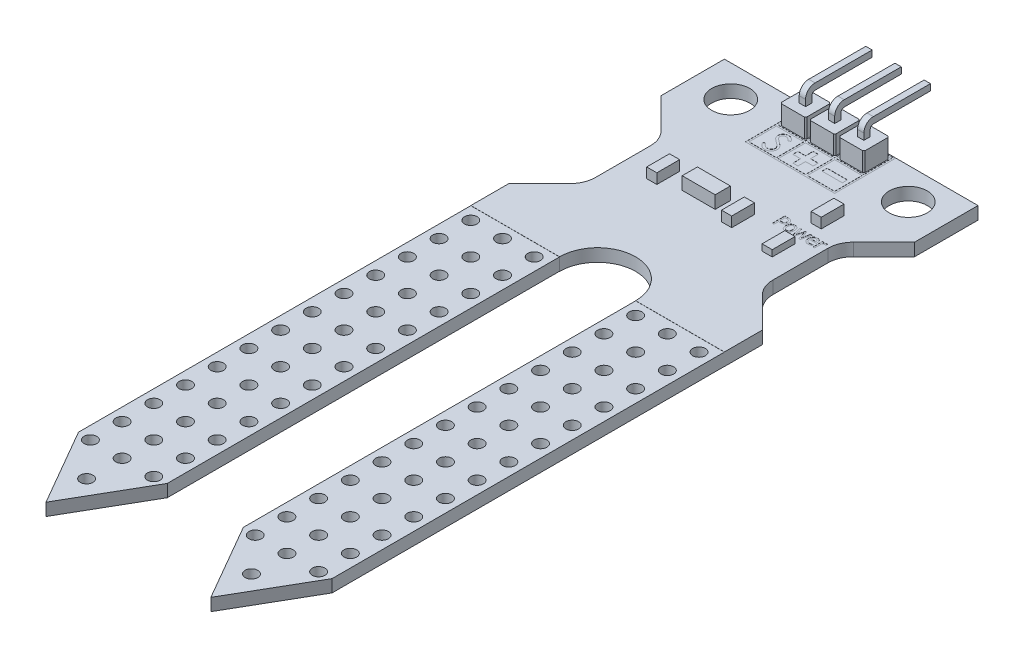
SolidWorks part; units mm, degrees
other "Camera2"
other "Camera4"
ref_plane "Front Plane" through (0, 0, 0) normal (0, 0, 1) x (1, 0, 0)
ref_plane "Top Plane" through (0, 0, 0) normal (0, 1, 0) x (1, 0, 0)
ref_plane "Right Plane" through (0, 0, 0) normal (1, 0, 0) x (0, 0, -1)
sketch "Sketch1" plane through (0, 0, 0) normal (0, 1, 0) x (1, 0, 0)
  line L0 (-10, 0) -> (10, 0)
  line L1 (-10, 0) -> (-10, -57) construction
  line L2 (-10, -57) -> (10, -57) construction
  line L3 (10, -57) -> (10, 0) construction
  line L4 (-10, 0) -> (-10, -5)
  line L5 (-10, -5) -> (-7.5858, -7.4142)
  line L6 (-7, -8.8284) -> (-7, -13.1716)
  line L7 (-7, -11) -> (-10, -11) construction
  line L8 (-10, -17) -> (-7.5858, -14.5858)
  line L9 (-7, -2.5) -> (7, -2.5) construction
  line L10 (0, 0) -> (0, -2.5) construction
  line L11 (-10, -17) -> (-10, -20)
  line L12 (-10, -20) -> (-3, -20)
  line L13 (10, 0) -> (10, -5)
  line L14 (7, -11) -> (10, -11) construction
  line L15 (10, -20) -> (3, -20)
  line L16 (10, -17) -> (10, -20)
  line L17 (10, -17) -> (7.5858, -14.5858)
  line L18 (7, -8.8284) -> (7, -13.1716)
  line L19 (10, -5) -> (7.5858, -7.4142)
  arc A0 (-7.5858, -7.4142) -> (-7, -8.8284) centre (-9, -8.8284) cw
  arc A1 (-7.5858, -14.5858) -> (-7, -13.1716) centre (-9, -13.1716) ccw
  arc A2 (7.5858, -14.5858) -> (7, -13.1716) centre (9, -13.1716) cw
  arc A3 (7.5858, -7.4142) -> (7, -8.8284) centre (9, -8.8284) ccw
  arc A4 (-3, -20) -> (3, -20) centre (0, -20) cw
  point P4 (0, 0)
  point P19 (0, -2.5)
  point P21 (-10, -2.5)
  dimension "D4" = 14
  dimension "D7" = 2
  dimension "D1" = 20
  dimension "D2" = 57
  dimension "D3" = 5
  dimension "D5" = 12
  dimension "D6" = 45
  dimension "D8" = 3
  dimension "D9" = 7
extrude "Base" add sketch "Sketch1" along normal mid plane 1
sketch "Sketch2" plane through (0, 0.5, 0) normal (0, 1, 0) x (1, 0, 0)
  line L0 (0, 0) -> (0, -17) construction
  line L1 (10, 0) -> (-10, 0) construction
  line L2 (7, -2.5) -> (-7, -2.5) construction
  circle A0 centre (-7, -2.5) radius 1.5
  arc A1 (3, -20) -> (-3, -20) centre (0, -20) ccw construction
  circle A2 centre (7, -2.5) radius 1.5
  point P12 (0, -2.5)
  dimension "D1" = 3
  dimension "D3" = 2.5
  dimension "D2" = 14
extrude "Holes" cut sketch "Sketch2" against normal up to next
sketch "Sketch3" plane through (0, 0, 0) normal (0, 1, 0) x (1, 0, 0)
  line L0 (0, 0) -> (0, -57) construction
  line L1 (-10, -20) -> (-3, -20)
  line L2 (-10, -20) -> (-10, -50.9378)
  line L3 (-10, -50.9378) -> (-6.5, -57)
  line L4 (-6.5, -57) -> (-3, -50.9378)
  line L5 (-3, -50.9378) -> (-3, -20)
  line L6 (-6.5, -20) -> (-6.5, -57) construction
  line L7 (-10, -50.9378) -> (-3, -50.9378) construction
  line L8 (10, -50.9378) -> (3, -50.9378) construction
  line L9 (6.5, -20) -> (6.5, -57) construction
  line L10 (3, -50.9378) -> (3, -20)
  line L11 (6.5, -57) -> (3, -50.9378)
  line L12 (10, -50.9378) -> (6.5, -57)
  line L13 (10, -20) -> (10, -50.9378)
  line L14 (10, -20) -> (3, -20)
  point P11 (0, 0)
  dimension "D1" = 57
  dimension "D2" = 30
extrude "Plate" add sketch "Sketch3" along normal mid plane 0.98
sketch "Sketch4" plane through (0, 0.49, 0) normal (0, 1, 0) x (1, 0, 0)
  line L0 (-9, -21) -> (-4, -21) construction
  line L1 (-9, -21) -> (-9, -23.5) construction
  line L2 (-9, -23.5) -> (-6.5, -23.5) construction
  line L3 (-6.5, -51) -> (-6.5, -53.8) construction
  line L4 (-6.5, -20) -> (-6.5, -21) construction
  line L5 (-3, -20) -> (-10, -20) construction
  line L6 (0, 72.5532) -> (0, -72.5532) construction
  line L7 (6.5, -20) -> (6.5, -21) construction
  line L8 (6.5, -51) -> (6.5, -53.8) construction
  line L9 (9, -23.5) -> (6.5, -23.5) construction
  line L10 (9, -21) -> (9, -23.5) construction
  line L11 (9, -21) -> (4, -21) construction
  circle A0 centre (-9, -21) radius 0.5
  circle A1 centre (-6.5, -21) radius 0.5
  circle A2 centre (-4, -21) radius 0.5
  circle A3 centre (-6.5, -23.5) radius 0.5
  circle A4 centre (-4, -23.5) radius 0.5
  circle A5 centre (-6.5, -26) radius 0.5
  circle A6 centre (-4, -26) radius 0.5
  circle A7 centre (-6.5, -28.5) radius 0.5
  circle A8 centre (-4, -28.5) radius 0.5
  circle A9 centre (-6.5, -31) radius 0.5
  circle A10 centre (-4, -31) radius 0.5
  circle A11 centre (-6.5, -33.5) radius 0.5
  circle A12 centre (-4, -33.5) radius 0.5
  circle A13 centre (-6.5, -36) radius 0.5
  circle A14 centre (-4, -36) radius 0.5
  circle A15 centre (-6.5, -38.5) radius 0.5
  circle A16 centre (-4, -38.5) radius 0.5
  circle A17 centre (-6.5, -41) radius 0.5
  circle A18 centre (-4, -41) radius 0.5
  circle A19 centre (-6.5, -43.5) radius 0.5
  circle A20 centre (-4, -43.5) radius 0.5
  circle A21 centre (-6.5, -46) radius 0.5
  circle A22 centre (-4, -46) radius 0.5
  circle A23 centre (-6.5, -48.5) radius 0.5
  circle A24 centre (-4, -48.5) radius 0.5
  circle A25 centre (-6.5, -51) radius 0.5
  circle A26 centre (-4, -51) radius 0.5
  circle A27 centre (-9, -23.5) radius 0.5
  circle A28 centre (-9, -26) radius 0.5
  circle A29 centre (-9, -28.5) radius 0.5
  circle A30 centre (-9, -31) radius 0.5
  circle A31 centre (-9, -33.5) radius 0.5
  circle A32 centre (-9, -36) radius 0.5
  circle A33 centre (-9, -38.5) radius 0.5
  circle A34 centre (-9, -41) radius 0.5
  circle A35 centre (-9, -43.5) radius 0.5
  circle A36 centre (-9, -46) radius 0.5
  circle A37 centre (-9, -48.5) radius 0.5
  circle A38 centre (-9, -51) radius 0.5
  circle A39 centre (-6.5, -53.8) radius 0.5
  circle A40 centre (6.5, -53.8) radius 0.5
  circle A41 centre (9, -51) radius 0.5
  circle A42 centre (9, -48.5) radius 0.5
  circle A43 centre (9, -46) radius 0.5
  circle A44 centre (9, -43.5) radius 0.5
  circle A45 centre (9, -41) radius 0.5
  circle A46 centre (9, -38.5) radius 0.5
  circle A47 centre (9, -36) radius 0.5
  circle A48 centre (9, -33.5) radius 0.5
  circle A49 centre (9, -31) radius 0.5
  circle A50 centre (9, -28.5) radius 0.5
  circle A51 centre (9, -26) radius 0.5
  circle A52 centre (9, -23.5) radius 0.5
  circle A53 centre (4, -51) radius 0.5
  circle A54 centre (6.5, -51) radius 0.5
  circle A55 centre (4, -48.5) radius 0.5
  circle A56 centre (6.5, -48.5) radius 0.5
  circle A57 centre (4, -46) radius 0.5
  circle A58 centre (6.5, -46) radius 0.5
  circle A59 centre (4, -43.5) radius 0.5
  circle A60 centre (6.5, -43.5) radius 0.5
  circle A61 centre (4, -41) radius 0.5
  circle A62 centre (6.5, -41) radius 0.5
  circle A63 centre (4, -38.5) radius 0.5
  circle A64 centre (6.5, -38.5) radius 0.5
  circle A65 centre (4, -36) radius 0.5
  circle A66 centre (6.5, -36) radius 0.5
  circle A67 centre (4, -33.5) radius 0.5
  circle A68 centre (6.5, -33.5) radius 0.5
  circle A69 centre (4, -31) radius 0.5
  circle A70 centre (6.5, -31) radius 0.5
  circle A71 centre (4, -28.5) radius 0.5
  circle A72 centre (6.5, -28.5) radius 0.5
  circle A73 centre (4, -26) radius 0.5
  circle A74 centre (6.5, -26) radius 0.5
  circle A75 centre (4, -23.5) radius 0.5
  circle A76 centre (6.5, -23.5) radius 0.5
  circle A77 centre (4, -21) radius 0.5
  circle A78 centre (6.5, -21) radius 0.5
  circle A79 centre (9, -21) radius 0.5
  point P89 (0, 0)
  point P170 (-6.5, -23.5)
  dimension "D1" = 1
  dimension "D8" = 2.8
  dimension "D2" = 5
  dimension "D3" = 1
  dimension "D6" = 2.5
  dimension "D4" = 3
  dimension "D5" = 13
extrude "Plate holes" cut sketch "Sketch4" against normal through all
sketch "Sketch5" plane through (0, 0.5, 0) normal (0, 1, 0) x (1, 0, 0)
  line L0 (-7, -2.5) -> (7, -2.5) construction
  line L1 (-3.2, -0.3) -> (-3.3, -0.4)
  line L2 (-3.2, -0.3) -> (-1.4, -0.3)
  line L3 (-3.3, -0.4) -> (-3.3, -2.2)
  line L4 (-3.2, -2.3) -> (-1.4, -2.3)
  line L5 (-1.3, -0.4) -> (-1.3, -2.2)
  line L6 (-3.3, -0.3) -> (-1.3, -2.3) construction
  line L7 (-3.3, -2.3) -> (-1.3, -0.3) construction
  line L8 (-1.4, -0.3) -> (-1.3, -0.4)
  line L9 (-3.3, -2.2) -> (-3.2, -2.3)
  line L10 (-1.3, -2.2) -> (-1.4, -2.3)
  line L11 (-0.9, -0.3) -> (-1, -0.4)
  line L12 (-0.9, -0.3) -> (0.9, -0.3)
  line L13 (-1, -0.4) -> (-1, -2.2)
  line L14 (-0.9, -2.3) -> (0.9, -2.3)
  line L15 (1, -0.4) -> (1, -2.2)
  line L16 (0.9, -0.3) -> (1, -0.4)
  line L17 (-1, -2.2) -> (-0.9, -2.3)
  line L18 (1, -2.2) -> (0.9, -2.3)
  line L19 (-1, -0.3) -> (1, -2.3) construction
  line L20 (-1, -2.3) -> (1, -0.3) construction
  line L21 (1.4, -0.3) -> (1.3, -0.4)
  line L22 (1.4, -0.3) -> (3.2, -0.3)
  line L23 (1.3, -0.4) -> (1.3, -2.2)
  line L24 (1.4, -2.3) -> (3.2, -2.3)
  line L25 (3.3, -0.4) -> (3.3, -2.2)
  line L26 (3.2, -0.3) -> (3.3, -0.4)
  line L27 (1.3, -2.2) -> (1.4, -2.3)
  line L28 (3.3, -2.2) -> (3.2, -2.3)
  line L29 (1.3, -0.3) -> (3.3, -2.3) construction
  line L30 (1.3, -2.3) -> (3.3, -0.3) construction
  line L31 (0, -2.3) -> (0, -2.5) construction
  point P4 (-2.3, -1.3)
  point P19 (0, -1.3)
  point P32 (2.3, -1.3)
  point P45 (0, 0)
  point P46 (0, 0)
  dimension "D1" = 2
  dimension "D2" = 3
  dimension "D3" = 0.2
  dimension "D8" = 0.3
extrude "Socket" add sketch "Sketch5" along normal blind 1.5
sketch "Sketch6" plane through (0, 2, 0) normal (0, 1, 0) x (1, 0, 0)
  line L0 (-2.3, -1.3) -> (-2.3, -0.3) construction
  line L1 (-2.6, -1.6) -> (-2, -1.6)
  line L2 (-2.6, -1.6) -> (-2.6, -1)
  line L3 (-2.6, -1) -> (-2, -1)
  line L4 (-2, -1.6) -> (-2, -1)
  line L5 (-2.6, -1.6) -> (-2, -1) construction
  line L6 (-2.6, -1) -> (-2, -1.6) construction
  line L8 (-1.4, -0.3) -> (-3.2, -0.3) construction
  line L9 (-2.3, -1.3) -> (-3.3, -1.3) construction
  line L10 (-3.3, -0.4) -> (-3.3, -2.2) construction
  point P0 (-2.3, -1.3)
  dimension "D1" = 0.6
sketch "Sketch7" plane through (0, 0, 0) normal (1, 0, 0) x (0, 0, -1)
  line L0 (-1.3, 2) -> (-1.3, 2.5) construction
  line L1 (-0.4, 2) -> (-2.2, 2) construction
  line L2 (-0.8, 3) -> (3.7, 3) construction
  line L3 (-1.05, 2) -> (-1.05, 2.5)
  line L4 (-0.8, 2.75) -> (3.7, 2.75)
  line L5 (-1.55, 2) -> (-1.55, 2.5)
  line L6 (-0.8, 3.25) -> (3.7, 3.25)
  line L7 (3.7, 3.25) -> (3.7, 2.75)
  line L8 (-1.05, 2) -> (-1.55, 2)
  arc A0 (-0.8, 3) -> (-1.3, 2.5) centre (-0.8, 2.5) ccw construction
  arc A1 (-0.8, 2.75) -> (-1.05, 2.5) centre (-0.8, 2.5) ccw
  arc A2 (-0.8, 3.25) -> (-1.55, 2.5) centre (-0.8, 2.5) ccw
  dimension "D2" = 0.5
  dimension "D1" = 0.5
  dimension "D3" = 5
  dimension "D4" = 0.25
  dimension "D5" = 0.25
extrude "Power pin" add sketch "Sketch7" along normal mid plane 0.5
pattern_linear "LPattern2" count 2 spacing 2.3 along (1, 0, 0) count 2 spacing 2.3 along (-1, 0, 0) of "Power pin"
sketch "Sketch9" plane through (0, 0.5, 0) normal (0, 1, 0) x (1, 0, 0)
  line L0 (-0.2, -3.8) -> (-0.2, -4.4)
  line L1 (-3.38, -2.38) -> (-1.22, -2.38)
  line L2 (-3.38, -2.38) -> (-3.38, -0.22)
  line L3 (-3.38, -0.22) -> (-1.22, -0.22)
  line L4 (-1.22, -2.38) -> (-1.22, -0.22)
  line L5 (-3.2, -2.3) -> (-1.4, -2.3) construction
  line L6 (-1.4, -0.3) -> (-3.2, -0.3) construction
  line L7 (-3.3, -0.4) -> (-3.3, -2.2) construction
  line L8 (-1.08, -2.38) -> (1.08, -2.38)
  line L9 (-1.08, -2.38) -> (-1.08, -0.22)
  line L10 (-1.08, -0.22) -> (1.08, -0.22)
  line L11 (1.08, -2.38) -> (1.08, -0.22)
  line L12 (1.22, -2.38) -> (3.38, -2.38)
  line L13 (1.22, -2.38) -> (1.22, -0.22)
  line L14 (1.22, -0.22) -> (3.38, -0.22)
  line L15 (3.38, -2.38) -> (3.38, -0.22)
  line L16 (-1.08, -4.68) -> (1.08, -4.68)
  line L17 (-1.08, -4.68) -> (-1.08, -2.52)
  line L18 (-1.08, -2.52) -> (1.08, -2.52)
  line L19 (1.08, -4.68) -> (1.08, -2.52)
  line L20 (1.22, -4.68) -> (3.38, -4.68)
  line L21 (1.22, -4.68) -> (1.22, -2.52)
  line L22 (1.22, -2.52) -> (3.38, -2.52)
  line L23 (3.38, -4.68) -> (3.38, -2.52)
  line L24 (-3.38, -4.68) -> (-1.22, -4.68)
  line L25 (-3.38, -4.68) -> (-3.38, -2.52)
  line L26 (-3.38, -2.52) -> (-1.22, -2.52)
  line L27 (-1.22, -4.68) -> (-1.22, -2.52)
  line L28 (-3.38, -0.22) -> (-3.38, -0.08) construction
  line L29 (-3.52, -0.08) -> (3.52, -0.08)
  line L30 (-3.52, -0.08) -> (-3.52, -4.82)
  line L31 (-3.52, -4.82) -> (3.52, -4.82)
  line L32 (3.52, -0.08) -> (3.52, -4.82)
  line L33 (-3.38, -0.22) -> (-3.52, -0.22) construction
  line L34 (-3.38, -4.68) -> (-3.38, -4.82) construction
  line L35 (3.38, -0.22) -> (3.52, -0.22) construction
  line L37 (1.5, -3.4) -> (1.5, -3.8)
  line L38 (1.5, -3.8) -> (3.1, -3.8)
  line L39 (3.1, -3.8) -> (3.1, -3.4)
  line L40 (3.1, -3.4) -> (1.5, -3.4)
  line L41 (-0.8, -3.4) -> (-0.8, -3.8)
  line L42 (-0.8, -3.8) -> (-0.2, -3.8)
  line L43 (0.8, -3.8) -> (0.8, -3.4)
  line L44 (0.8, -3.4) -> (0.2, -3.4)
  line L45 (-0.2, -2.8) -> (0.2, -2.8)
  line L46 (-0.2, -2.8) -> (-0.2, -3.4)
  line L47 (-0.2, -4.4) -> (0.2, -4.4)
  line L48 (0.2, -2.8) -> (0.2, -3.4)
  line L49 (-0.2, -3.4) -> (-0.8, -3.4)
  line L50 (0.2, -3.8) -> (0.2, -4.4)
  line L51 (0.2, -3.8) -> (0.8, -3.8)
  line L52 (3.3426, -8.9613) -> (3.2278, -8.9613)
  line L53 (3.2278, -8.9613) -> (3.2278, -9.3284)
  line L54 (3.2278, -9.3284) -> (3.1013, -9.3284)
  line L55 (3.1013, -9.3284) -> (3.1013, -8.3284)
  line L56 (3.1013, -8.3284) -> (3.353, -8.3284)
  line L57 (3.3402, -8.4424) -> (3.2278, -8.4424)
  line L58 (3.2278, -8.4424) -> (3.2278, -8.8474)
  line L59 (3.2278, -8.8474) -> (3.3202, -8.8474)
  line L60 (5.4937, -8.5816) -> (5.3072, -9.3284)
  line L61 (5.3072, -9.3284) -> (5.1926, -9.3284)
  line L62 (5.1926, -9.3284) -> (5.0127, -8.7527)
  line L63 (5.0127, -8.7527) -> (4.8341, -9.3284)
  line L64 (4.8341, -9.3284) -> (4.7201, -9.3284)
  line L65 (4.7201, -9.3284) -> (4.5316, -8.5816)
  line L66 (4.5316, -8.5816) -> (4.6622, -8.5816)
  line L67 (4.6622, -8.5816) -> (4.7905, -9.1599)
  line L68 (4.7905, -9.1599) -> (4.9652, -8.5816)
  line L69 (4.9652, -8.5816) -> (5.0674, -8.5816)
  line L70 (5.0674, -8.5816) -> (5.2466, -9.1599)
  line L71 (5.2466, -9.1599) -> (5.3631, -8.5816)
  line L72 (5.3631, -8.5816) -> (5.4937, -8.5816)
  line L73 (6.2025, -8.8935) -> (6.2025, -8.9613)
  line L74 (6.2025, -8.9613) -> (5.6835, -8.9613)
  line L75 (6.1826, -9.1386) -> (6.1899, -9.1386)
  line L76 (6.1899, -9.1386) -> (6.1899, -9.2782)
  line L77 (5.6835, -8.8601) -> (6.0759, -8.8601)
  line L78 (6.7215, -8.7082) -> (6.715, -8.7082)
  line L79 (6.4557, -8.7962) -> (6.4557, -9.3284)
  line L80 (6.4557, -9.3284) -> (6.3291, -9.3284)
  line L81 (6.3291, -9.3284) -> (6.3291, -8.5816)
  line L82 (6.3291, -8.5816) -> (6.4557, -8.5816)
  line L83 (6.4557, -8.5816) -> (6.4557, -8.6925)
  line L84 (6.7215, -8.5853) -> (6.7215, -8.7082)
  line L85 (-2.7938, -4.1828) -> (-2.6417, -4.0915)
  line L86 (-1.7554, -2.9885) -> (-1.9014, -3.0992)
  spline S0 degree 3 poles (3.7342, -8.6326) (3.7344, -8.6541) (3.7312, -8.6861) (3.7215, -8.7275) (3.7111, -8.7571) (3.6985, -8.7853) (3.678, -8.8198) (3.6595, -8.8432) (3.6454, -8.8569) knots 0 0 0 0 0.260382 0.387742 0.514624 0.640166 0.761611 1 1 1 1
  spline S1 degree 3 poles (3.6454, -8.8569) (3.6282, -8.8742) (3.5993, -8.8968) (3.5564, -8.9209) (3.5216, -8.936) (3.4831, -8.9475) (3.4234, -8.9589) (3.3757, -8.9613) (3.3426, -8.9613) knots 0 0 0 0 0.221352 0.332954 0.446759 0.566652 0.698228 1 1 1 1
  spline S2 degree 3 poles (3.353, -8.3284) (3.3806, -8.3286) (3.4203, -8.3298) (3.4708, -8.3364) (3.504, -8.3429) (3.5348, -8.3514) (3.5726, -8.3658) (3.5988, -8.3803) (3.6149, -8.3915) knots 0 0 0 0 0.301816 0.435226 0.557564 0.673138 0.784559 1 1 1 1
  spline S3 degree 3 poles (3.6149, -8.3915) (3.6332, -8.404) (3.6584, -8.4259) (3.6857, -8.4609) (3.7033, -8.4893) (3.7173, -8.5207) (3.7309, -8.5683) (3.7342, -8.6065) (3.7342, -8.6326) knots 0 0 0 0 0.236653 0.354095 0.472429 0.593575 0.720488 1 1 1 1
  spline S4 degree 3 poles (3.5949, -8.6358) (3.5948, -8.6193) (3.5931, -8.5951) (3.5852, -8.5648) (3.5772, -8.5443) (3.567, -8.5256) (3.5496, -8.5031) (3.5337, -8.4887) (3.5216, -8.4811) knots 0 0 0 0 0.276791 0.40364 0.52478 0.643556 0.760318 1 1 1 1
  spline S5 degree 3 poles (3.5216, -8.4811) (3.5108, -8.4736) (3.4927, -8.465) (3.4672, -8.456) (3.4461, -8.4509) (3.4232, -8.4469) (3.3877, -8.4431) (3.3597, -8.4425) (3.3402, -8.4424) knots 0 0 0 0 0.208675 0.317736 0.431465 0.554189 0.688523 1 1 1 1
  spline S6 degree 3 poles (3.3202, -8.8474) (3.345, -8.8475) (3.3804, -8.8462) (3.4247, -8.8404) (3.4525, -8.8348) (3.4773, -8.8269) (3.5069, -8.813) (3.5261, -8.7981) (3.5374, -8.7869) knots 0 0 0 0 0.321499 0.457599 0.578008 0.68845 0.794252 1 1 1 1
  spline S7 degree 3 poles (3.5374, -8.7869) (3.5471, -8.7772) (3.5599, -8.7612) (3.5734, -8.7381) (3.5815, -8.7202) (3.5877, -8.7012) (3.5936, -8.6731) (3.595, -8.6509) (3.5949, -8.6358) knots 0 0 0 0 0.248146 0.366465 0.48252 0.601376 0.726647 1 1 1 1
  spline S8 degree 3 poles (4.4684, -8.9554) (4.4684, -8.9855) (4.4659, -9.0294) (4.4562, -9.0856) (4.4463, -9.124) (4.4336, -9.1597) (4.4176, -9.1926) (4.399, -9.2228) (4.3776, -9.2501) (4.3538, -9.2745) (4.328, -9.2959) (4.3001, -9.3137) (4.2705, -9.3285) (4.2389, -9.3398) (4.1934, -9.3507) (4.1577, -9.3539) (4.1335, -9.3537) knots 0 0 0 0 0.153334 0.223622 0.290634 0.354958 0.416591 0.476661 0.53556 0.593318 0.64991 0.70585 0.761767 0.818223 0.876674 1 1 1 1
  spline S9 degree 3 poles (4.1335, -9.3537) (4.1086, -9.354) (4.0722, -9.3506) (4.0256, -9.3395) (3.9936, -9.3274) (3.9635, -9.3124) (3.9356, -9.2939) (3.91, -9.2719) (3.8864, -9.2468) (3.8656, -9.2187) (3.8472, -9.1882) (3.8318, -9.1552) (3.8191, -9.1199) (3.8096, -9.0821) (3.7997, -9.0273) (3.7976, -8.9845) (3.7975, -8.9554) knots 0 0 0 0 0.126624 0.185762 0.243469 0.300245 0.356694 0.413633 0.472086 0.531601 0.591562 0.653162 0.716692 0.782593 0.851506 1 1 1 1
  spline S10 degree 3 poles (3.7975, -8.9554) (3.7974, -8.9255) (3.7998, -8.8818) (3.8099, -8.8258) (3.8199, -8.7875) (3.8327, -8.7518) (3.8488, -8.7188) (3.8676, -8.6884) (3.8892, -8.6608) (3.9134, -8.6364) (3.9393, -8.6148) (3.9673, -8.5967) (3.9969, -8.5816) (4.0286, -8.5706) (4.0739, -8.5591) (4.1095, -8.5563) (4.1335, -8.5563) knots 0 0 0 0 0.152158 0.222426 0.289447 0.353383 0.415396 0.47586 0.535165 0.593567 0.650568 0.706628 0.762633 0.819341 0.87748 1 1 1 1
  spline S11 degree 3 poles (4.1335, -8.5563) (4.1577, -8.5561) (4.1934, -8.5593) (4.239, -8.5702) (4.2705, -8.5818) (4.3001, -8.5967) (4.328, -8.6148) (4.3539, -8.6361) (4.3776, -8.6607) (4.399, -8.6882) (4.4177, -8.7185) (4.4335, -8.7514) (4.4464, -8.7871) (4.4562, -8.8254) (4.4658, -8.8816) (4.4685, -8.9255) (4.4684, -8.9554) knots 0 0 0 0 0.123252 0.181668 0.238205 0.294238 0.350327 0.406885 0.464849 0.523978 0.584011 0.64591 0.70988 0.776851 0.847428 1 1 1 1
  spline S12 degree 3 poles (4.3418, -8.9554) (4.3418, -8.9328) (4.3406, -8.9) (4.3344, -8.8581) (4.3289, -8.8299) (4.3211, -8.8041) (4.3119, -8.7806) (4.3007, -8.7595) (4.2882, -8.7406) (4.2737, -8.7241) (4.2581, -8.7094) (4.2407, -8.6974) (4.2221, -8.6873) (4.202, -8.6796) (4.1725, -8.672) (4.1492, -8.6704) (4.1335, -8.6702) knots 0 0 0 0 0.168865 0.245064 0.316508 0.383414 0.446027 0.505125 0.561591 0.615756 0.66878 0.721159 0.77321 0.826581 0.882058 1 1 1 1
  spline S13 degree 3 poles (4.1335, -8.6702) (4.1177, -8.6705) (4.0943, -8.672) (4.0648, -8.6796) (4.0445, -8.6873) (4.0257, -8.6973) (4.0083, -8.7095) (3.9925, -8.7241) (3.9779, -8.7405) (3.9653, -8.7595) (3.9541, -8.7806) (3.9446, -8.8041) (3.9372, -8.83) (3.9313, -8.8581) (3.9253, -8.9) (3.924, -8.9328) (3.9241, -8.9554) knots 0 0 0 0 0.118168 0.173523 0.227235 0.279605 0.331868 0.385137 0.439506 0.495848 0.554814 0.617473 0.684091 0.755478 0.831508 1 1 1 1
  spline S14 degree 3 poles (3.9241, -8.9554) (3.924, -8.9773) (3.9254, -9.0093) (3.9314, -9.0502) (3.9372, -9.0779) (3.9446, -9.1037) (3.9542, -9.127) (3.9653, -9.1484) (3.9779, -9.1677) (3.9924, -9.1847) (4.0083, -9.1996) (4.0258, -9.2119) (4.0444, -9.2223) (4.0647, -9.2302) (4.0943, -9.2377) (4.1177, -9.2398) (4.1335, -9.2398) knots 0 0 0 0 0.164255 0.239131 0.309846 0.376265 0.439182 0.498828 0.556224 0.611938 0.665761 0.718524 0.771581 0.825693 0.881275 1 1 1 1
  spline S15 degree 3 poles (4.1335, -9.2398) (4.1492, -9.2396) (4.1723, -9.2379) (4.2017, -9.2305) (4.2216, -9.2224) (4.2403, -9.2126) (4.2575, -9.2003) (4.2734, -9.1858) (4.2877, -9.169) (4.3007, -9.1502) (4.3117, -9.1289) (4.3209, -9.1053) (4.3286, -9.0796) (4.3345, -9.0517) (4.3405, -9.0102) (4.3418, -8.9777) (4.3418, -8.9554) knots 0 0 0 0 0.117813 0.172983 0.22624 0.278888 0.331025 0.384578 0.439285 0.496204 0.555922 0.618729 0.685842 0.756642 0.832586 1 1 1 1
  spline S16 degree 3 poles (5.9337, -9.3411) (5.9055, -9.3412) (5.8641, -9.3381) (5.8111, -9.3279) (5.775, -9.3167) (5.7412, -9.3027) (5.7101, -9.2851) (5.6813, -9.2647) (5.6553, -9.241) (5.6322, -9.2144) (5.6118, -9.1852) (5.5948, -9.1532) (5.581, -9.1185) (5.57, -9.0813) (5.5596, -9.0266) (5.5571, -8.9838) (5.557, -8.9546) knots 0 0 0 0 0.138011 0.202055 0.263381 0.322416 0.38038 0.437398 0.494395 0.551685 0.609308 0.668092 0.728495 0.79127 0.85721 1 1 1 1
  spline S17 degree 3 poles (5.557, -8.9546) (5.5572, -8.9257) (5.5594, -8.8831) (5.5697, -8.8286) (5.5802, -8.791) (5.5936, -8.7557) (5.6101, -8.7227) (5.6296, -8.692) (5.6519, -8.6639) (5.6768, -8.6387) (5.7036, -8.6166) (5.7323, -8.5978) (5.7628, -8.5826) (5.7953, -8.5708) (5.8417, -8.5592) (5.8783, -8.5565) (5.9029, -8.5563) knots 0 0 0 0 0.146259 0.214368 0.279724 0.343168 0.404962 0.465739 0.526162 0.585964 0.644156 0.701412 0.75874 0.816144 0.875498 1 1 1 1
  spline S18 degree 3 poles (5.9029, -8.5563) (5.9248, -8.5562) (5.9569, -8.5583) (5.9978, -8.567) (6.0259, -8.5756) (6.0519, -8.5873) (6.085, -8.606) (6.1064, -8.6252) (6.1197, -8.6388) knots 0 0 0 0 0.275081 0.402883 0.524391 0.643013 0.760604 1 1 1 1
  spline S19 degree 3 poles (6.1197, -8.6388) (6.1335, -8.6529) (6.151, -8.6774) (6.17, -8.7133) (6.1819, -8.7432) (6.1912, -8.776) (6.2005, -8.8262) (6.2024, -8.866) (6.2025, -8.8935) knots 0 0 0 0 0.215476 0.326952 0.443318 0.566199 0.699559 1 1 1 1
  spline S20 degree 3 poles (5.6835, -8.9613) (5.6834, -8.9817) (5.6853, -9.0114) (5.6924, -9.0494) (5.6994, -9.0752) (5.7087, -9.0991) (5.72, -9.1211) (5.7335, -9.1411) (5.7491, -9.1592) (5.7663, -9.1753) (5.7854, -9.1891) (5.8059, -9.2009) (5.828, -9.2107) (5.8518, -9.2179) (5.8863, -9.2251) (5.9133, -9.2274) (5.9318, -9.2272) knots 0 0 0 0 0.14768 0.215278 0.279761 0.341367 0.400591 0.458795 0.516089 0.572912 0.629707 0.686449 0.744451 0.804022 0.866557 1 1 1 1
  spline S21 degree 3 poles (5.9318, -9.2272) (5.9591, -9.227) (6.012, -9.2213) (6.0623, -9.2043) (6.0856, -9.1943) knots 0 0 0 0 0.518474 1 1 1 1
  spline S22 degree 3 poles (6.0856, -9.1943) (6.1053, -9.1856) (6.1392, -9.1694) (6.17, -9.1482) (6.1826, -9.1386) knots 0 0 0 0 0.577022 1 1 1 1
  spline S23 degree 3 poles (6.1899, -9.2782) (6.1816, -9.2814) (6.1686, -9.2865) (6.1502, -9.2938) (6.1209, -9.3056) (6.096, -9.3149) (6.0759, -9.3203) knots 0 0 0 0 0.218524 0.346372 0.486611 1 1 1 1
  spline S24 degree 3 poles (6.0759, -9.3203) (6.0539, -9.3262) (6.0265, -9.3331) (5.9927, -9.3384) (5.9675, -9.3404) (5.9477, -9.341) (5.9337, -9.3411) knots 0 0 0 0 0.475716 0.586628 0.710511 1 1 1 1
  spline S25 degree 3 poles (6.0759, -8.8601) (6.0758, -8.8446) (6.0738, -8.8223) (6.069, -8.7938) (6.0641, -8.7749) (6.0586, -8.7574) (6.049, -8.7366) (6.0406, -8.7221) (6.0334, -8.7137) knots 0 0 0 0 0.299598 0.432962 0.557938 0.676116 0.788008 1 1 1 1
  spline S26 degree 3 poles (6.0334, -8.7137) (6.0262, -8.7046) (6.0135, -8.6924) (5.9937, -8.6794) (5.9771, -8.6716) (5.9589, -8.6651) (5.9307, -8.6589) (5.9081, -8.6578) (5.8926, -8.6575) knots 0 0 0 0 0.22125 0.334031 0.45002 0.571455 0.703086 1 1 1 1
  spline S27 degree 3 poles (5.8926, -8.6575) (5.8772, -8.6575) (5.8549, -8.6593) (5.8267, -8.6653) (5.808, -8.672) (5.7907, -8.6802) (5.7689, -8.6936) (5.7538, -8.7059) (5.7447, -8.7151) knots 0 0 0 0 0.282218 0.410057 0.529593 0.645 0.761338 1 1 1 1
  spline S28 degree 3 poles (5.7447, -8.7151) (5.7355, -8.7243) (5.7235, -8.7396) (5.7099, -8.7614) (5.7019, -8.7788) (5.695, -8.7971) (5.6882, -8.8242) (5.6844, -8.8454) (5.6835, -8.8601) knots 0 0 0 0 0.242625 0.360813 0.479168 0.599866 0.725826 1 1 1 1
  spline S29 degree 3 poles (6.715, -8.7082) (6.7052, -8.7082) (6.6831, -8.7082) (6.6609, -8.7082) (6.6485, -8.7082) knots 0 0 0 0 0.440476 1 1 1 1
  spline S30 degree 3 poles (6.6485, -8.7082) (6.6318, -8.7082) (6.6064, -8.7111) (6.5734, -8.7203) (6.5486, -8.73) (6.5243, -8.7425) (6.4921, -8.7632) (6.4697, -8.7821) (6.4557, -8.7962) knots 0 0 0 0 0.230943 0.349875 0.471982 0.597666 0.726082 1 1 1 1
  spline S31 degree 3 poles (6.4557, -8.6925) (6.476, -8.6742) (6.5058, -8.6494) (6.546, -8.6216) (6.5728, -8.6067) (6.5982, -8.5954) (6.6306, -8.5852) (6.6552, -8.5815) (6.6715, -8.5816) knots 0 0 0 0 0.33091 0.468651 0.589975 0.700616 0.804235 1 1 1 1
  spline S32 degree 3 poles (6.6715, -8.5816) (6.681, -8.5815) (6.6978, -8.5818) (6.7144, -8.5844) (6.7215, -8.5853) knots 0 0 0 0 0.571302 1 1 1 1
  spline S33 degree 3 poles (-2.6417, -4.0915) (-2.6153, -4.1373) (-2.5737, -4.2014) (-2.5083, -4.2741) (-2.4595, -4.3167) (-2.4089, -4.3502) (-2.3395, -4.3818) (-2.2835, -4.3916) (-2.2465, -4.3915) knots 0 0 0 0 0.304646 0.438547 0.562322 0.677433 0.786897 1 1 1 1
  spline S34 degree 3 poles (-2.2465, -4.3915) (-2.2152, -4.3918) (-2.1685, -4.3863) (-2.1086, -4.369) (-2.0661, -4.3506) (-2.0265, -4.3283) (-1.9917, -4.3014) (-1.9617, -4.2712) (-1.9371, -4.2376) (-1.9182, -4.2014) (-1.8989, -4.152) (-1.8943, -4.1124) (-1.8938, -4.0865) knots 0 0 0 0 0.18093 0.270088 0.360156 0.448343 0.532666 0.613834 0.693982 0.772716 0.849335 1 1 1 1
  spline S35 degree 3 poles (-1.8938, -4.0865) (-1.8937, -4.056) (-1.906, -3.9924) (-1.9388, -3.9366) (-1.9584, -3.9098) knots 0 0 0 0 0.477158 1 1 1 1
  spline S36 degree 3 poles (-1.9584, -3.9098) (-1.975, -3.8879) (-2.003, -3.8547) (-2.0466, -3.8124) (-2.0846, -3.7769) (-2.1279, -3.7407) (-2.1931, -3.6875) (-2.2463, -3.6492) (-2.2829, -3.6228) knots 0 0 0 0 0.18953 0.299198 0.418926 0.548376 0.688136 1 1 1 1
  spline S37 degree 3 poles (-2.2829, -3.6228) (-2.3193, -3.5973) (-2.3703, -3.5595) (-2.434, -3.5102) (-2.4737, -3.4782) (-2.5078, -3.4491) (-2.5433, -3.4173) (-2.5654, -3.3933) (-2.5779, -3.378) knots 0 0 0 0 0.347082 0.495568 0.628357 0.74552 0.845831 1 1 1 1
  spline S38 degree 3 poles (-2.5779, -3.378) (-2.5938, -3.3574) (-2.616, -3.3257) (-2.6397, -3.2806) (-2.6534, -3.2464) (-2.665, -3.2118) (-2.6755, -3.1646) (-2.6786, -3.1282) (-2.6785, -3.1039) knots 0 0 0 0 0.262559 0.388264 0.512667 0.633722 0.755394 1 1 1 1
  spline S39 degree 3 poles (-2.6785, -3.1039) (-2.6786, -3.0663) (-2.6714, -3.0102) (-2.6475, -2.9396) (-2.6227, -2.8901) (-2.5906, -2.8448) (-2.5536, -2.8034) (-2.5095, -2.7685) (-2.461, -2.738) (-2.408, -2.7142) (-2.3334, -2.69) (-2.2742, -2.6844) (-2.235, -2.6838) knots 0 0 0 0 0.16578 0.24628 0.327461 0.408797 0.489715 0.571376 0.655523 0.741019 0.826547 1 1 1 1
  spline S40 degree 3 poles (-2.235, -2.6838) (-2.1928, -2.6838) (-2.1296, -2.6915) (-2.0498, -2.7196) (-2.0017, -2.7434) (-1.9641, -2.7671) (-1.9354, -2.7887) (-1.9064, -2.8136) (-1.8767, -2.8418) (-1.8469, -2.8736) (-1.8052, -2.9219) (-1.775, -2.9609) (-1.7554, -2.9885) knots 0 0 0 0 0.213252 0.31883 0.426794 0.483646 0.543604 0.608308 0.677127 0.750686 0.828713 1 1 1 1
  spline S41 degree 3 poles (-1.9014, -3.0992) (-1.9182, -3.0772) (-1.9435, -3.0462) (-1.9773, -3.0074) (-2.0012, -2.9831) (-2.0236, -2.9611) (-2.0452, -2.9423) (-2.0659, -2.9265) (-2.092, -2.9096) (-2.1248, -2.8929) (-2.1799, -2.8738) (-2.2237, -2.8686) (-2.253, -2.8685) knots 0 0 0 0 0.189629 0.274184 0.352183 0.423199 0.488551 0.548473 0.60144 0.701198 0.799592 1 1 1 1
  spline S42 degree 3 poles (-2.253, -2.8685) (-2.2888, -2.8679) (-2.3413, -2.8756) (-2.4042, -2.9041) (-2.4435, -2.933) (-2.4763, -2.9674) (-2.5082, -3.0202) (-2.5169, -3.066) (-2.5169, -3.0963) knots 0 0 0 0 0.275903 0.402371 0.528414 0.650356 0.765895 1 1 1 1
  spline S43 degree 3 poles (-2.5169, -3.0963) (-2.5175, -3.1157) (-2.5131, -3.1445) (-2.5034, -3.1823) (-2.4919, -3.2105) (-2.4761, -3.239) (-2.4466, -3.2805) (-2.4185, -3.3094) (-2.3983, -3.3289) knots 0 0 0 0 0.214746 0.322939 0.434116 0.553412 0.686073 1 1 1 1
  spline S44 degree 3 poles (-2.3983, -3.3289) (-2.389, -3.3374) (-2.3721, -3.3513) (-2.3453, -3.3713) (-2.3178, -3.3922) (-2.2849, -3.4164) (-2.2304, -3.4552) (-2.1871, -3.4865) (-2.1563, -3.5081) knots 0 0 0 0 0.124952 0.218094 0.333502 0.468789 0.624938 1 1 1 1
  spline S45 degree 3 poles (-2.1563, -3.5081) (-2.1185, -3.5356) (-2.0638, -3.5758) (-1.9964, -3.6317) (-1.9524, -3.671) (-1.9129, -3.7088) (-1.8782, -3.7456) (-1.848, -3.7811) (-1.8155, -3.8267) (-1.7824, -3.8826) (-1.7448, -3.9722) (-1.7323, -4.0427) (-1.7323, -4.089) knots 0 0 0 0 0.187773 0.272396 0.351321 0.424335 0.491909 0.554233 0.611268 0.716348 0.81454 1 1 1 1
  spline S46 degree 3 poles (-1.7323, -4.089) (-1.7318, -4.121) (-1.737, -4.1684) (-1.7523, -4.2296) (-1.7693, -4.2733) (-1.79, -4.3158) (-1.8163, -4.3562) (-1.8468, -4.3952) (-1.8818, -4.4318) (-1.9201, -4.4654) (-1.9606, -4.4953) (-2.0033, -4.5202) (-2.048, -4.5405) (-2.0948, -4.5564) (-2.1606, -4.5721) (-2.212, -4.5763) (-2.2465, -4.5762) knots 0 0 0 0 0.121775 0.18092 0.240256 0.300114 0.361146 0.423501 0.488669 0.553954 0.617581 0.680238 0.742187 0.804663 0.868259 1 1 1 1
  spline S47 degree 3 poles (-2.2465, -4.5762) (-2.2735, -4.5763) (-2.3137, -4.573) (-2.3662, -4.5642) (-2.4041, -4.5538) (-2.4411, -4.5413) (-2.4772, -4.5258) (-2.5123, -4.5072) (-2.5467, -4.4859) (-2.5802, -4.4612) (-2.6126, -4.4324) (-2.6448, -4.4004) (-2.676, -4.3642) (-2.7068, -4.3244) (-2.7477, -4.2645) (-2.7758, -4.2163) (-2.7938, -4.1828) knots 0 0 0 0 0.113696 0.169178 0.224159 0.27872 0.333794 0.389241 0.445822 0.503704 0.564294 0.627975 0.695038 0.765373 0.839611 1 1 1 1
  point P0 (-2.3, -2.38)
  point P9 (-2.3, -2.3)
  point P46 (2.3, -2.52)
  point P49 (2.3, -3.4)
  point P50 (1.5, -3.6)
  point P51 (1.22, -3.6)
  point P57 (-0.8, -3.6)
  point P58 (0, -2.52)
  point P59 (-1.08, -3.6)
  point P66 (0, -2.8)
  dimension "D1" = 0.08
  dimension "D2" = 0.08
  dimension "D3" = 0.14
  dimension "D4" = 3
  dimension "D6" = 0.14
  dimension "D7" = 0.14
  dimension "D10" = 1.6
  dimension "D11" = 0.4
  dimension "D12" = 1.6
  dimension "D13" = 0.4
  dimension "D14" = 1.6
  dimension "D15" = 0.28
  dimension "D16" = 0.28
  dimension "D5" = 2
extrude "Cut-Extrude3" cut sketch "Sketch9" against normal blind 0.01 contours L32 L29 L30 L31 L27 L24 L25 L26 L23 L20 L21 L22 L19 L16 L17 L18 L15 L12 L13 L14 L11 L8 L9 L10 L4 L1 L2 L3 | L50 L51 L43 L44 L48 L45 L46 L49 L41 L42 L0 L47 | L39 L40 L37 L38 | S47 S46 S45 S44 S43 S42 S41 L86 S40 S39 S38 S37 S36 S35 S34 S33 L85 | S3 S2 L56 L55 L54 L53 L52 S1 S0 S7 S6 L59 L58 L57 S5 S4 | S11 S10 S9 S8 S15 S14 S13 S12 | L72 L71 L70 L69 L68 L67 L66 L65 L64 L63 L62 L61 L60 | S24 S23 L76 L75 S22 S21 S20 L74 L73 S19 S18 S17 S16 S28 S27 S26 S25 L77 | S32 S31 L83 L82 L81 L80 L79 S30 S29 L78 L84
sketch "Sketch10" plane through (0, 0.5, 0) normal (0, 1, 0) x (1, 0, 0)
  line L1 (-2.7, -9.4284) -> (-0.1, -9.4284)
  line L2 (-2.7, -9.4284) -> (-2.7, -10.6284)
  line L3 (-2.7, -10.6284) -> (-0.1, -10.6284)
  line L4 (-0.1, -9.4284) -> (-0.1, -10.6284)
  line L5 (-2.7, -9.4284) -> (-0.1, -10.6284) construction
  line L6 (-2.7, -10.6284) -> (-0.1, -9.4284) construction
  point P4 (-1.4, -10.0284)
  point P5 (-2.7, -10.0284)
  dimension "D1" = 2.6
  dimension "D2" = 1.2
  dimension "D3" = 4.3
  dimension "D4" = 1.2
extrude "Big resistor" add sketch "Sketch10" along normal blind 1
sketch "Sketch11" plane through (0, 0.5, 0) normal (0, 1, 0) x (1, 0, 0)
  line L0 (1, -9.4284) -> (1.8, -9.4284)
  line L1 (-4.9, -9.4284) -> (-4.1, -9.4284)
  line L2 (-4.9, -9.4284) -> (-4.9, -11.2284)
  line L3 (-4.9, -11.2284) -> (-4.1, -11.2284)
  line L4 (-4.1, -9.4284) -> (-4.1, -11.2284)
  line L5 (-4.9, -9.4284) -> (-4.1, -11.2284) construction
  line L6 (-4.9, -11.2284) -> (-4.1, -9.4284) construction
  line L7 (1, -9.4284) -> (1, -11.2284)
  line L8 (1, -11.2284) -> (1.8, -11.2284)
  line L9 (1.8, -9.4284) -> (1.8, -11.2284)
  line L10 (1, -9.4284) -> (1.8, -11.2284) construction
  line L11 (1, -11.2284) -> (1.8, -9.4284) construction
  line L12 (4.6163, -5.9816) -> (5.4163, -5.9816)
  line L13 (4.6163, -5.9816) -> (4.6163, -7.7816)
  line L14 (4.6163, -7.7816) -> (5.4163, -7.7816)
  line L15 (5.4163, -5.9816) -> (5.4163, -7.7816)
  line L16 (4.6163, -5.9816) -> (5.4163, -7.7816) construction
  line L17 (4.6163, -7.7816) -> (5.4163, -5.9816) construction
  line L18 (-7, -8.8284) -> (-7, -13.1716) construction
  line L19 (-0.1, -9.4284) -> (-2.7, -9.4284) construction
  line L20 (-0.1, -10.6284) -> (-0.1, -9.4284) construction
  line L21 (4.9652, -8.5816) -> (5.0674, -8.5816) construction
  line L22 (4.9652, -8.5816) -> (5.0674, -8.5816) construction
  point P4 (-4.5, -10.3284)
  point P5 (-5.2635, -9.9208)
  point P6 (-5.3425, -10.2765)
  point P11 (1.4, -10.3284)
  point P12 (1.0699, -10.2765)
  point P13 (-4.6456, -10.2765)
  point P18 (5.0163, -6.8816)
  point P19 (4.8555, -6.9531)
  point P20 (1.4011, -10.2765)
  point P27 (5.0163, -7.7816)
  point P30 (5.0163, -8.5816)
  dimension "D1" = 0.8
  dimension "D2" = 1.8
  dimension "D3" = 0.8
  dimension "D4" = 1.8
  dimension "D5" = 0.8
  dimension "D6" = 1.8
  dimension "D7" = 2.5
  dimension "D8" = 1.5
  dimension "D9" = 0.8
extrude "Small resistor" add sketch "Sketch11" along normal blind 0.8
sketch "Sketch12" plane through (0, 0.5, 0) normal (0, 1, 0) x (1, 0, 0)
  line L0 (7, -13.1716) -> (7, -8.8284) construction
  line L1 (4.6, -9.8284) -> (5.4, -9.8284)
  line L2 (4.6, -9.8284) -> (4.6, -11.6284)
  line L3 (4.6, -11.6284) -> (5.4, -11.6284)
  line L4 (5.4, -9.8284) -> (5.4, -11.6284)
  line L5 (4.6, -9.8284) -> (5.4, -11.6284) construction
  line L6 (4.6, -11.6284) -> (5.4, -9.8284) construction
  line L7 (4.8341, -9.3284) -> (4.7201, -9.3284) construction
  point P4 (5, -10.7284)
  point P7 (7, -11)
  dimension "D1" = 0.8
  dimension "D2" = 1.8
  dimension "D3" = 2
  dimension "D4" = 0.5
extrude "Light" add sketch "Sketch12" along normal blind 0.5
